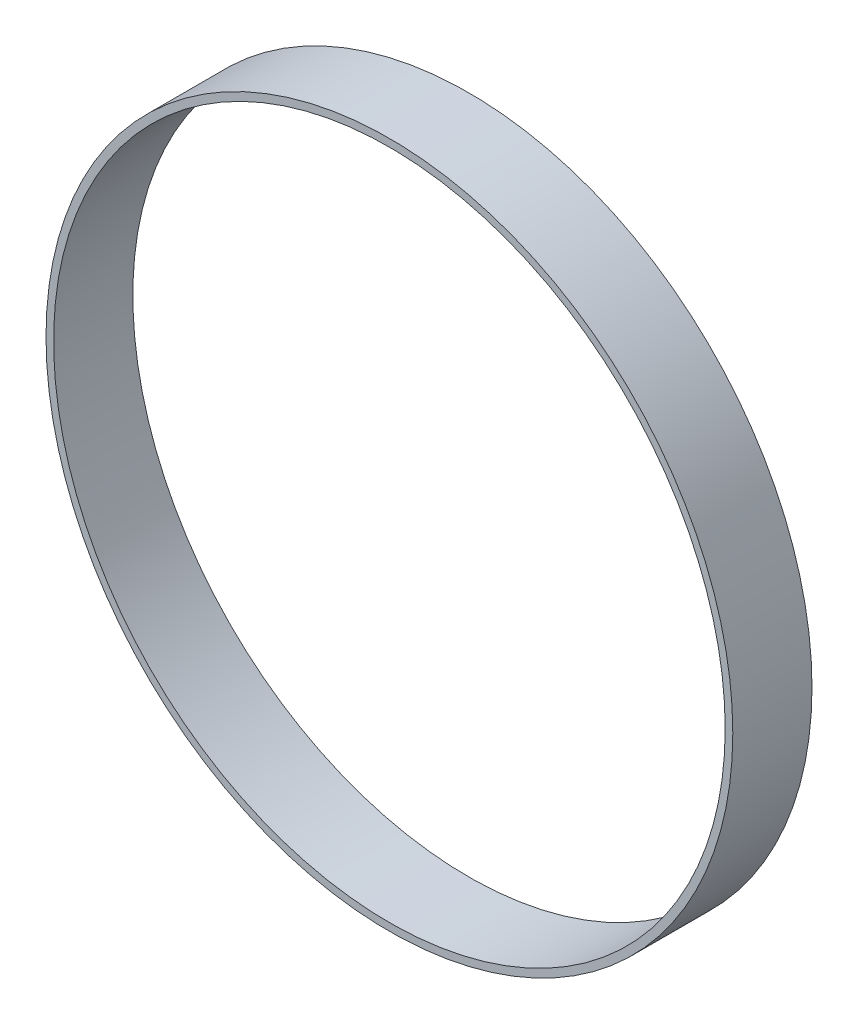
SolidWorks part; units mm, degrees
ref_plane "Płaszczyzna przednia" through (0, 0, 0) normal (0, 0, 1) x (1, 0, 0)
ref_plane "Płaszczyzna górna" through (0, 0, 0) normal (0, 1, 0) x (1, 0, 0)
ref_plane "Płaszczyzna prawa" through (0, 0, 0) normal (1, 0, 0) x (0, 0, -1)
sketch "Szkic1" plane through (0, 0, 0) normal (0, 0, 1) x (1, 0, 0)
  circle A0 centre (49.2925, 35.3457) radius 54.2
  circle A1 centre (49.2925, 35.3457) radius 53
extrude "Dodanie-wyciągnięcie1" add sketch "Szkic1" against normal blind 12.5
